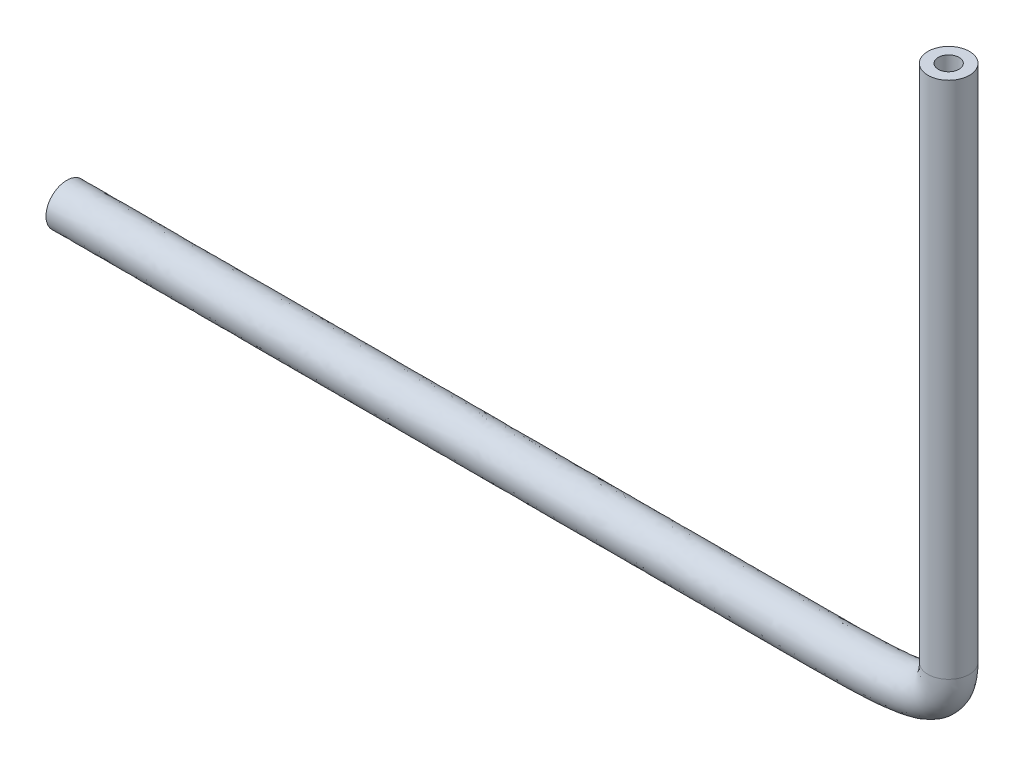
SolidWorks part; units mm, degrees
other "Pipe1"
material "PTFE (general)"
ref_plane "Front" through (0, 0, 0) normal (0, 0, 1) x (1, 0, 0)
ref_plane "Top" through (0, 0, 0) normal (0, 1, 0) x (1, 0, 0)
ref_plane "Right" through (0, 0, 0) normal (1, 0, 0) x (0, 0, -1)
sketch "PipeSke" plane through (0, 0, 0) normal (0, 0, 1) x (1, 0, 0)
  line L0 (0, 0) -> (-28, 0)
  line L1 (6, 21.7045) -> (6, 1.7045)
  spline S0 degree 3 poles (0, 0) (4.6199, 0) (6, 0.036) (6, 1.7045) knots 0 0 0 0 1 1 1 1
  dimension "D1" = 28
  dimension "D2" = 20
sketch "PipeRing" plane through (0, 0, 0) normal (1, 0, 0) x (0, 0, -1)
  circle A0 centre (0, 0) radius 0.8
  circle A1 centre (0, 0) radius 0.4
  dimension "D1" = 1.6
  dimension "D2" = 0.8
sweep "Pipe" add profiles "PipeRing" path "PipeSke"
